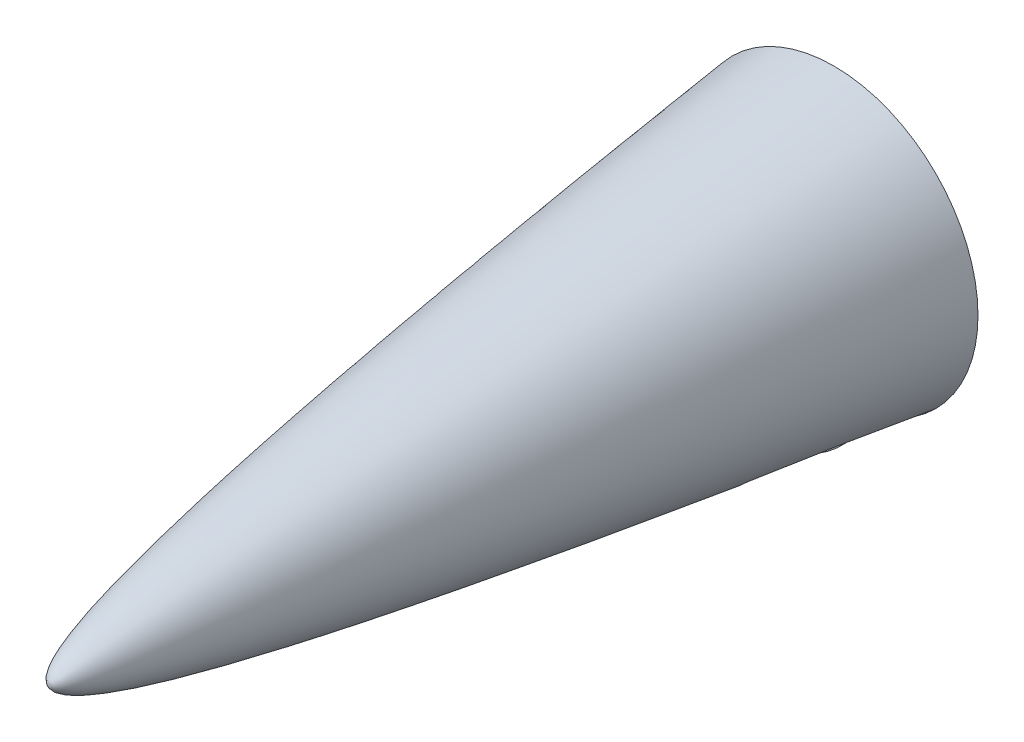
SolidWorks part; units mm, degrees
ref_plane "Front Plane" through (0, 0, 0) normal (0, 0, 1) x (1, 0, 0)
ref_plane "Top Plane" through (0, 0, 0) normal (0, 1, 0) x (1, 0, 0)
ref_plane "Right Plane" through (0, 0, 0) normal (1, 0, 0) x (0, 0, -1)
sketch "Sketch1" plane through (0, 0, 0) normal (1, 0, 0) x (0, 0, -1)
  line L0 (0, 76.2) -> (0, 0)
  line L1 (0, 0) -> (-415.2337, 0)
  spline S0 degree 4 poles (-415.2337, 0) (-415.2481, 0.2458) (-415.2336, 0.5718) (-415.156, 0.9866) (-414.9738, 1.5084) (-414.7837, 1.9177) (-414.5025, 2.3917) (-414.0876, 2.9526) (-413.4763, 3.6291) (-412.5193, 4.4969) (-410.9485, 5.6602) (-408.1406, 7.3392) (-404.0806, 9.2637) (-398.9337, 11.295) (-392.9887, 13.3243) (-386.9479, 15.1788) (-379.3079, 17.3347) (-369.068, 19.9703) (-356.2305, 22.9644) (-340.7859, 26.2499) (-324.2982, 29.4999) (-303.6435, 33.3299) (-278.8067, 37.6339) (-249.7764, 42.3459) (-216.554, 47.4216) (-187.4488, 51.656) (-162.4919, 55.1662) (-141.6738, 58.0245) (-125.0341, 60.2713) (-108.3496, 62.4887) (-91.7331, 64.6659) (-74.9859, 66.8293) (-60.5359, 68.6735) (-47.8173, 70.2787) (-37.738, 71.5429) (-28.7809, 72.6574) (-19.5894, 73.7989) (-3.2618, 75.8049) (6.2953, 76.9692) (23.753, 79.0825) (31.5744, 80.0152) (38.4813, 80.8447) (39.9364, 81.0151) (41.7948, 81.2381) knots 0 0 0 0 0 0.002093 0.002794 0.00359 0.004723 0.00595 0.007505 0.009554 0.012517 0.016992 0.024213 0.037521 0.050931 0.06434 0.077977 0.091613 0.118886 0.154852 0.190819 0.226785 0.262751 0.334684 0.406617 0.478549 0.550482 0.586448 0.622415 0.658381 0.694347 0.730314 0.76628 0.802246 0.82023 0.838213 0.856196 0.874179 0.910145 0.955073 0.977536 0.988768 1 1 1 1 1 construction
  spline S1 degree 4 poles (-415.2337, 0) (-415.2481, 0.2458) (-415.2336, 0.5718) (-415.156, 0.9866) (-414.9738, 1.5084) (-414.7837, 1.9177) (-414.5025, 2.3917) (-414.0876, 2.9526) (-413.4763, 3.6291) (-412.5193, 4.4969) (-410.9485, 5.6602) (-408.1406, 7.3392) (-404.0806, 9.2637) (-398.9337, 11.295) (-392.9887, 13.3243) (-386.9479, 15.1788) (-379.3079, 17.3347) (-369.068, 19.9703) (-356.2305, 22.9644) (-340.7859, 26.2499) (-324.2982, 29.4999) (-303.6435, 33.3299) (-278.8067, 37.6339) (-249.7764, 42.3459) (-216.554, 47.4216) (-187.4488, 51.656) (-162.4919, 55.1662) (-141.6738, 58.0245) (-125.0341, 60.2713) (-108.3496, 62.4887) (-91.7331, 64.6659) (-74.9859, 66.8293) (-60.5359, 68.6735) (-47.8173, 70.2787) (-37.738, 71.5429) (-28.7809, 72.6574) (-19.5894, 73.7989) (-9.539, 75.0337) (-3.7956, 75.7369) (0, 76.2) knots 0 0 0 0 0 0.002093 0.002794 0.00359 0.004723 0.00595 0.007505 0.009554 0.012517 0.016992 0.024213 0.037521 0.050931 0.06434 0.077977 0.091613 0.118886 0.154852 0.190819 0.226785 0.262751 0.334684 0.406617 0.478549 0.550482 0.586448 0.622415 0.658381 0.694347 0.730314 0.76628 0.802246 0.82023 0.838213 0.856196 0.874179 0.910145 0.910145 0.910145 0.910145 0.910145
  dimension "D1" = 76.2
revolve "Revolve1" add sketch "Sketch1" angle 360 about L1
equation "\"n\"= 0.5"
equation "\"R\"= 2'base radius"
equation "\"L\"= 16.5'overall length"
